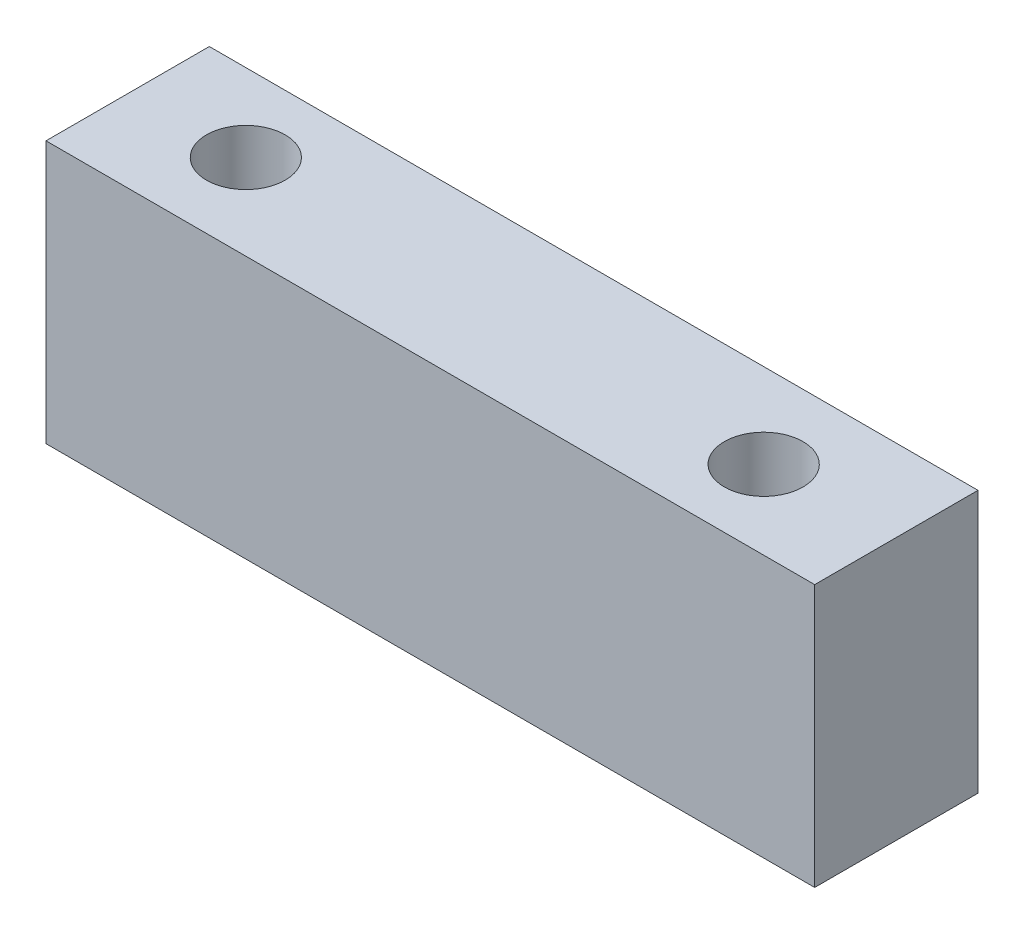
SolidWorks part; units mm, degrees
ref_plane "前视基准面" through (0, 0, 0) normal (0, 0, 1) x (1, 0, 0)
ref_plane "上视基准面" through (0, 0, 0) normal (0, 1, 0) x (1, 0, 0)
ref_plane "右视基准面" through (0, 0, 0) normal (1, 0, 0) x (0, 0, -1)
other "Configuration Table"
sketch "草图1" plane through (0, 0, 0) normal (0, 1, 0) x (1, 0, 0)
  line L1 (-24.7873, 4.4797) -> (4.517, 4.4797)
  line L2 (-24.7873, 4.4797) -> (-24.7873, -1.7464)
  line L3 (-24.7873, -1.7464) -> (4.517, -1.7464)
  line L4 (4.517, 4.4797) -> (4.517, -1.7464)
  line L5 (-24.7873, 4.4797) -> (4.517, -1.7464) construction
  line L6 (-24.7873, -1.7464) -> (4.517, 4.4797) construction
  circle A0 centre (-20.4273, 1.5113) radius 1.5
  circle A1 centre (-0.4273, 1.2536) radius 1.5
  point P0 (-10.1351, 1.3666)
  dimension "D1" = 3
  dimension "D2" = 3
  dimension "D4" = 3
  dimension "D5" = 3.2577
  dimension "D3" = 20
extrude "凸台-拉伸1" add sketch "草图1" along normal blind 10
